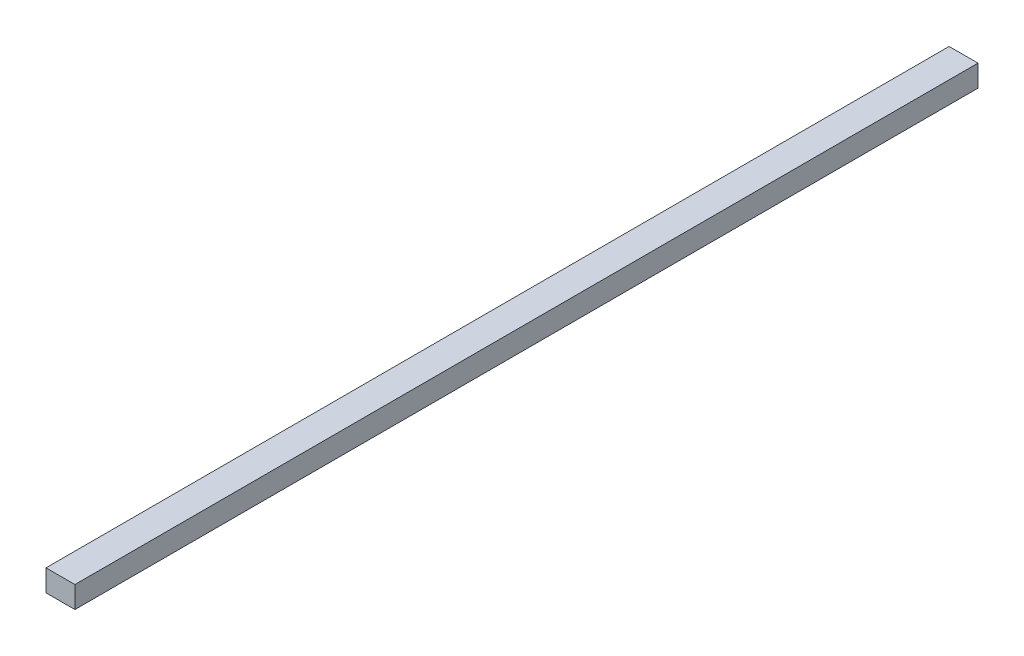
SolidWorks part; units mm, degrees
ref_plane "Front Plane" through (0, 0, 0) normal (0, 0, 1) x (1, 0, 0)
ref_plane "Top Plane" through (0, 0, 0) normal (0, 1, 0) x (1, 0, 0)
ref_plane "Right Plane" through (0, 0, 0) normal (1, 0, 0) x (0, 0, -1)
other "Configuration Table"
sketch "Sketch1" plane through (0, 0, 0) normal (0, 0, 1) x (1, 0, 0)
  line L1 (394, 1176) -> (410, 1176)
  line L2 (394, 1176) -> (394, 1188)
  line L3 (394, 1188) -> (410, 1188)
  line L4 (410, 1176) -> (410, 1188)
extrude "PRESS_uc_catal_lama_2_1" add sketch "Sketch1" against normal blind 500 from offset 50 separate body
